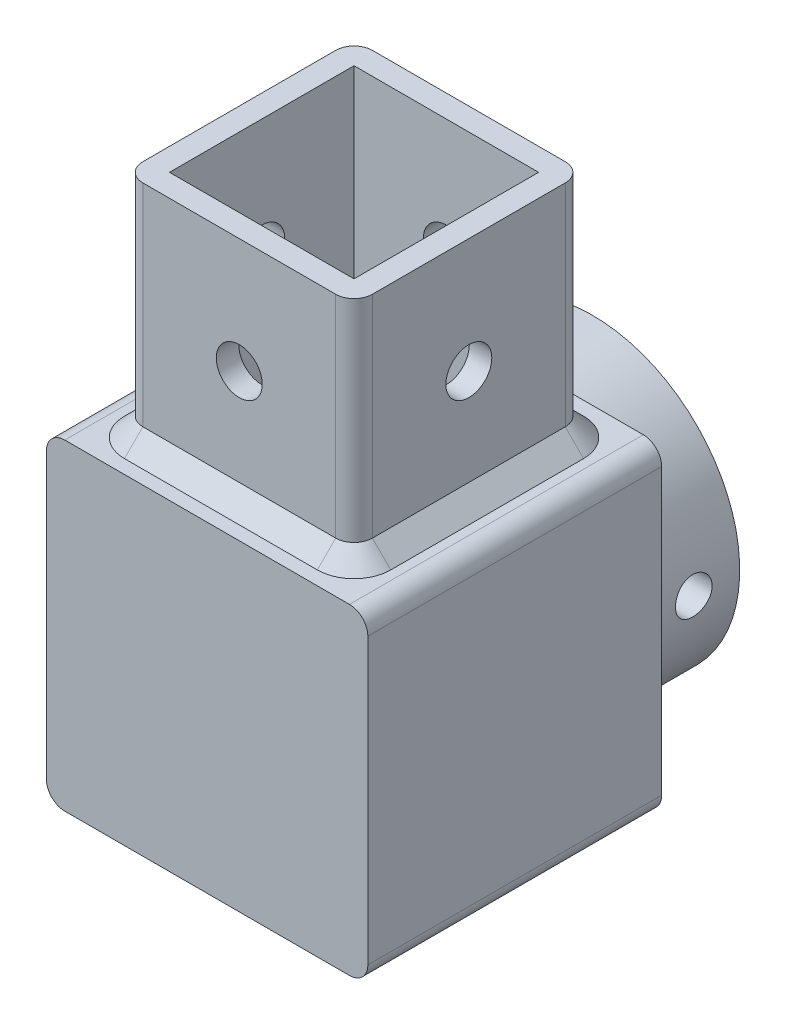
SolidWorks part; units mm, degrees
ref_plane "Front Plane" through (0, 0, 0) normal (0, 0, 1) x (1, 0, 0)
ref_plane "Top Plane" through (0, 0, 0) normal (0, 1, 0) x (1, 0, 0)
ref_plane "Right Plane" through (0, 0, 0) normal (1, 0, 0) x (0, 0, -1)
sketch "Sketch1" plane through (0, 0, 0) normal (0, 0, 1) x (1, 0, 0)
  line L1 (17.5, 17.5) -> (-17.5, 17.5)
  line L2 (17.5, 17.5) -> (17.5, -17.5)
  line L3 (17.5, -17.5) -> (-17.5, -17.5)
  line L4 (-17.5, 17.5) -> (-17.5, -17.5)
  line L5 (17.5, 17.5) -> (-17.5, -17.5) construction
  line L6 (17.5, -17.5) -> (-17.5, 17.5) construction
  point P0 (0, 0)
  dimension "D1" = 35
  dimension "D2" = 35
extrude "Boss-Extrude1" add sketch "Sketch1" along normal blind 32
sketch "Sketch2" plane through (0, 0, 0) normal (0, 0, -1) x (-1, 0, 0)
  circle A0 centre (0, 0) radius 16
  circle A1 centre (0, 0) radius 10.1
  dimension "D1" = 32
  dimension "D2" = 20.2
extrude "Boss-Extrude2" add sketch "Sketch2" along normal blind 10
sketch "Sketch3" plane through (0, 0, 0) normal (0, 0, -1) x (-1, 0, 0)
  circle A0 centre (0, 0) radius 10
  dimension "D1" = 20
extrude "Cut-Extrude1" cut sketch "Sketch3" against normal blind 25
sketch "Sketch4" plane through (0, 0, 0) normal (0, 1, 0) x (1, 0, 0)
  line L0 (-16, 5) -> (16, 5) construction
  line L1 (-16, 10) -> (-16, 0) construction
  line L2 (16, 0) -> (16, 10) construction
  circle A0 centre (0, 5) radius 2
  point P13 (0, 4)
  dimension "D1" = 4
extrude "Cut-Extrude2" cut sketch "Sketch4" against normal mid plane 40
sketch "Sketch5" plane through (0, 0, 0) normal (1, 0, 0) x (0, 0, -1)
  line L0 (0, 0) -> (10, 0) construction
  line L2 (10, -16) -> (10, 16) construction
  circle A0 centre (5, 0) radius 2
  point P7 (4, 0)
  dimension "D1" = 4
extrude "Cut-Extrude3" cut sketch "Sketch5" against normal mid plane 40
sketch "Sketch6" plane through (0, 17.5, 0) normal (0, 1, 0) x (1, 0, 0)
  line L0 (-17.5, -16) -> (17.5, -16) construction
  line L1 (-17.5, -32) -> (-17.5, 0) construction
  line L2 (17.5, -32) -> (17.5, 0) construction
  line L3 (0, 0) -> (0, -32) construction
  line L5 (17.5, -32) -> (-17.5, -32) construction
  line L6 (12.5, -3.5) -> (-12.5, -3.5)
  line L7 (12.5, -3.5) -> (12.5, -28.5)
  line L8 (12.5, -28.5) -> (-12.5, -28.5)
  line L9 (-12.5, -3.5) -> (-12.5, -28.5)
  line L10 (12.5, -3.5) -> (-12.5, -28.5) construction
  line L11 (12.5, -28.5) -> (-12.5, -3.5) construction
  line L12 (10.05, -5.95) -> (-10.05, -5.95)
  line L13 (10.05, -5.95) -> (10.05, -26.05)
  line L14 (10.05, -26.05) -> (-10.05, -26.05)
  line L15 (-10.05, -5.95) -> (-10.05, -26.05)
  line L16 (10.05, -5.95) -> (-10.05, -26.05) construction
  line L17 (10.05, -26.05) -> (-10.05, -5.95) construction
  point P8 (-0.1102, -16)
  point P11 (0, -16)
  point P16 (0, -16)
  dimension "D1" = 25
  dimension "D2" = 25
  dimension "D3" = 20.1
extrude "Boss-Extrude3" add sketch "Sketch6" along normal blind 25
sketch "Sketch7" plane through (0, 0, 28.5) normal (0, 0, 1) x (1, 0, 0)
  line L0 (0, 42.5) -> (0, 17.5) construction
  line L1 (-12.5, 42.5) -> (12.5, 42.5) construction
  line L2 (-12.5, 17.5) -> (12.5, 17.5) construction
  line L3 (12.5, 30) -> (-12.5, 30) construction
  line L4 (12.5, 42.5) -> (12.5, 17.5) construction
  line L5 (-12.5, 42.5) -> (-12.5, 17.5) construction
  circle A0 centre (0, 30) radius 2.5
  dimension "D1" = 5
extrude "Cut-Extrude4" cut sketch "Sketch7" against normal through all
sketch "Sketch8" plane through (12.5, 0, 0) normal (1, 0, 0) x (0, 0, -1)
  line L0 (-16, 42.5) -> (-16, 17.5) construction
  line L1 (-28.5, 42.5) -> (-3.5, 42.5) construction
  line L2 (-32, 17.5) -> (0, 17.5) construction
  line L3 (-28.5, 30) -> (-3.5, 30) construction
  line L4 (-28.5, 42.5) -> (-28.5, 17.5) construction
  line L5 (-3.5, 42.5) -> (-3.5, 17.5) construction
  circle A0 centre (-16, 30) radius 2.5
  dimension "D1" = 5
extrude "Cut-Extrude5" cut sketch "Sketch8" against normal blind 25
fillet "Fillet1" radius 2 6 edges at (12.5, 30, 28.5) (12.5, 30, 3.5) (-12.5, 30, 3.5) (-12.5, 30, 28.5) (-17.5, 17.5, 16) (17.5, 17.5, 16)
fillet "Fillet2" radius 2 2 edges at (-17.5, -17.5, 16) (17.5, -17.5, 16)
fillet "Fillet3" radius 1 1 edges at (-16, 0, 0)
chamfer "Chamfer1" distance 2 angle 45 8 edges at (0, 17.5, 28.5) (0, 17.5, 3.5) (11.9142, 17.5, 27.9142) (11.9142, 17.5, 4.0858) (12.5, 17.5, 16) (-11.9142, 17.5, 4.0858) (-11.9142, 17.5, 27.9142) (-12.5, 17.5, 16)
